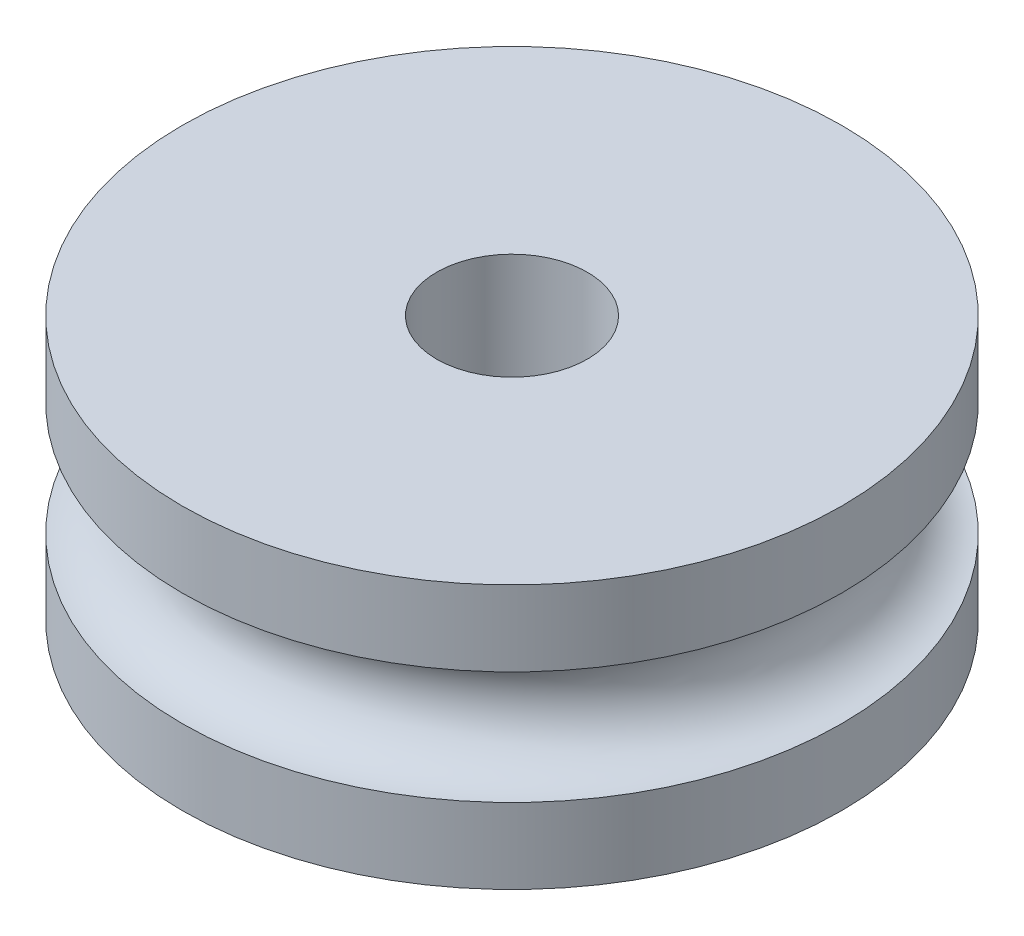
SolidWorks part; units mm, degrees
ref_plane "Front Plane" through (0, 0, 0) normal (0, 0, 1) x (1, 0, 0)
ref_plane "Top Plane" through (0, 0, 0) normal (0, 1, 0) x (1, 0, 0)
ref_plane "Right Plane" through (0, 0, 0) normal (1, 0, 0) x (0, 0, -1)
sketch "Sketch1" plane through (0, 0, 0) normal (0, 0, 1) x (1, 0, 0)
  line L0 (55, 0) -> (-55, 0) construction
  line L7 (-17.5, -7) -> (-17.5, -3)
  line L8 (-17.5, 7) -> (-4, 7)
  line L11 (0, 7) -> (0, -7) construction
  line L12 (-17.5, 7) -> (-17.5, 3)
  line L15 (-17.5, -7) -> (-4, -7)
  line L17 (-4, 7) -> (-4, -7)
  arc A2 (-17.5, 3) -> (-17.5, -3) centre (-17.5, 0) cw
  point P1 (-5.3422, 7)
  dimension "D2" = 3
  dimension "D4" = 8
  dimension "D1" = 4
  dimension "D3" = 35
revolve "Revolve1" add sketch "Sketch1" angle 360 about L11
